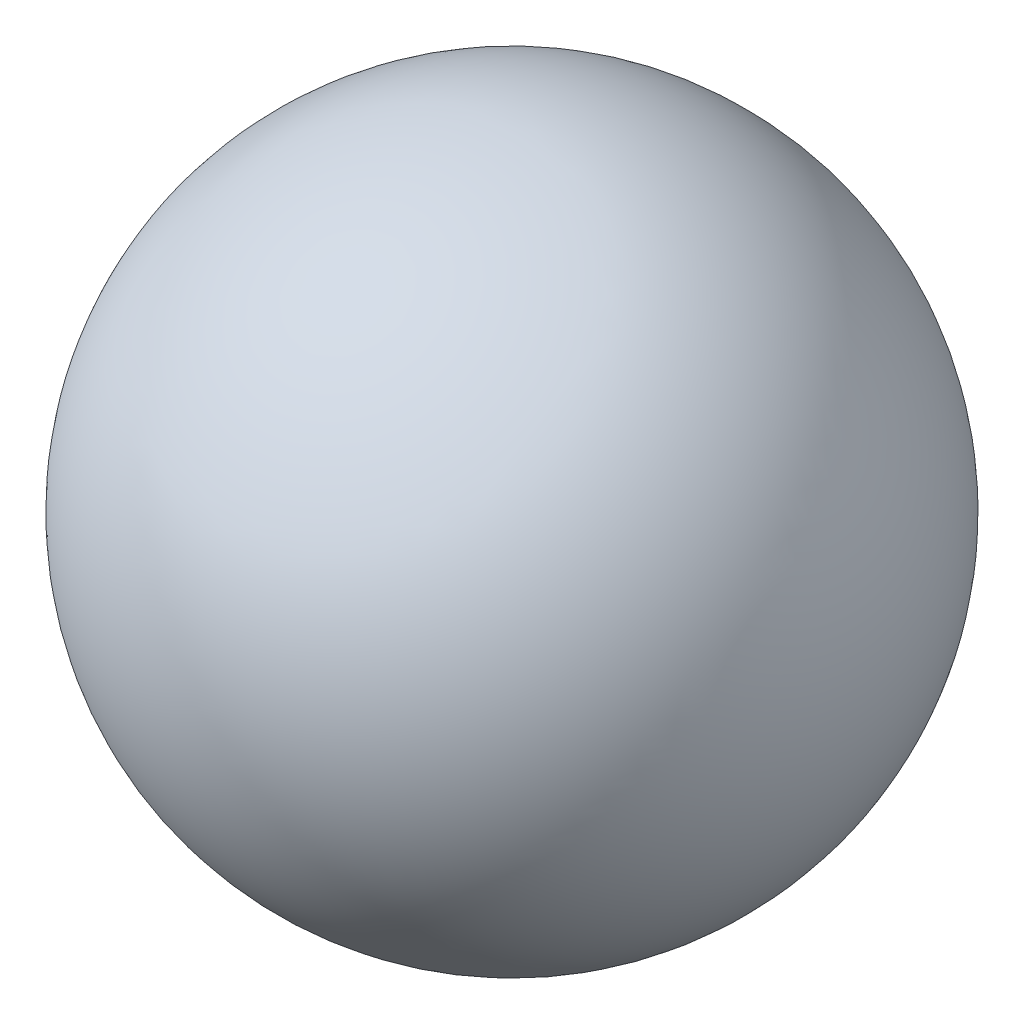
SolidWorks part; units mm, degrees
ref_plane "Piano frontale" through (0, 0, 0) normal (0, 0, 1) x (1, 0, 0)
ref_plane "Piano superiore" through (0, 0, 0) normal (0, 1, 0) x (1, 0, 0)
ref_plane "Piano destro" through (0, 0, 0) normal (1, 0, 0) x (0, 0, -1)
ref_plane "Piano1" through (0, 0, 0) normal (0, 0, 1) x (1, 0, 0)
sketch "Schizzo1" plane through (0, 0, 0) normal (0, 0, 1) x (1, 0, 0)
  line L0 (14.1595, 51.25) -> (3.8405, 51.25)
  line L1 (14.1595, 51.25) -> (3.8405, 51.25) construction
  arc A0 (3.8405, 51.25) -> (14.1595, 51.25) centre (9, 51.25) cw
revolve "Rivoluzione1" add sketch "Schizzo1" angle 360 about L1
